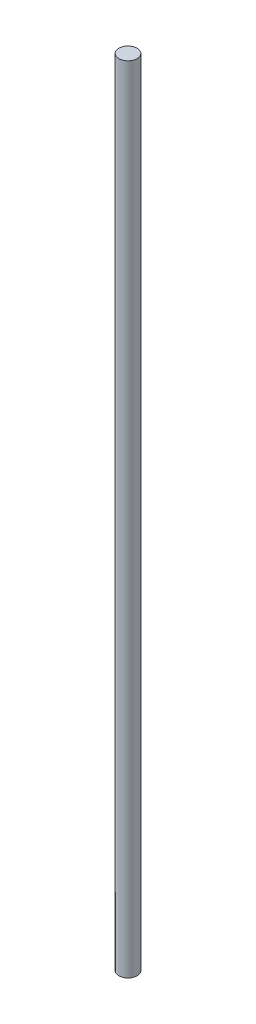
SolidWorks part; units mm, degrees
material "AISI 1020"
ref_plane "Plano frontal" through (0, 0, 0) normal (0, 0, 1) x (1, 0, 0)
ref_plane "Plano superior" through (0, 0, 0) normal (0, 1, 0) x (1, 0, 0)
ref_plane "Plano direito" through (0, 0, 0) normal (1, 0, 0) x (0, 0, -1)
sketch "Esboço2" plane through (0, 0, 0) normal (0, 1, 0) x (1, 0, 0)
  circle A0 centre (0, 0) radius 4
  dimension "D1" = 8
extrude "Ressalto-extrusão1" add sketch "Esboço2" along normal mid plane 350
